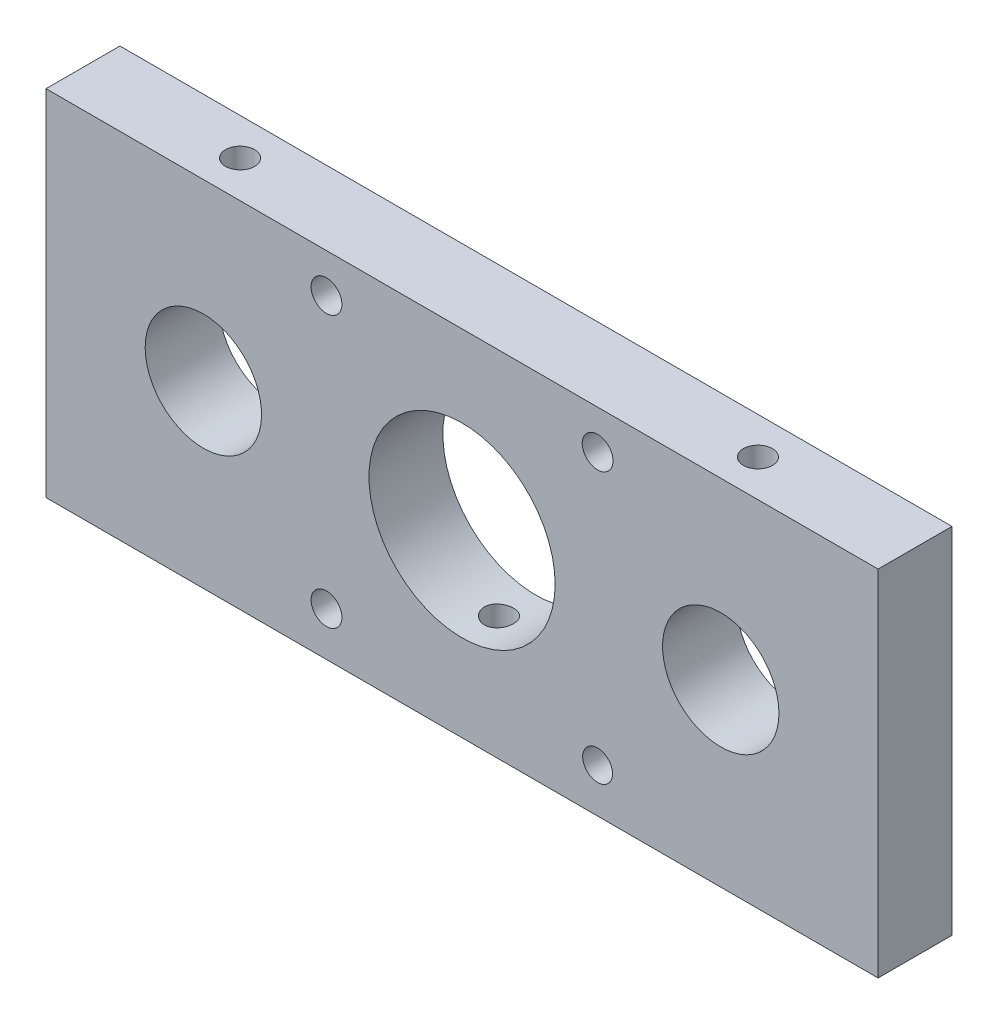
SolidWorks part; units mm, degrees
ref_plane "Plano frontal" through (0, 0, 0) normal (0, 0, 1) x (1, 0, 0)
ref_plane "Plano superior" through (0, 0, 0) normal (0, 1, 0) x (1, 0, 0)
ref_plane "Plano direito" through (0, 0, 0) normal (1, 0, 0) x (0, 0, -1)
sketch "Esboço1" plane through (0, 0, 0) normal (0, 0, 1) x (1, 0, 0)
  line L0 (71.505, 27) -> (-71.505, -27) construction
  line L1 (-71.505, 27) -> (71.505, 27)
  line L2 (-71.505, 27) -> (-71.505, -27)
  line L3 (-71.505, -27) -> (71.505, -27)
  line L4 (71.505, 27) -> (71.505, -27)
  dimension "D1" = 143.01
  dimension "D2" = 54
extrude "Ressalto-extrusão1" add sketch "Esboço1" along normal blind 10
sketch "Esboço14" plane through (-71.505, 0, 0) normal (-1, 0, 0) x (0, 0, 1)
  line L1 (0, 27) -> (-2.7, 27)
  line L2 (0, 27) -> (0, -30.87)
  line L3 (0, -30.87) -> (-2.7, -30.87)
  line L4 (-2.7, 27) -> (-2.7, -30.87)
  dimension "D1" = 2.7
extrude "Ressalto-extrusão3" add sketch "Esboço14" against normal up to surface (143.01 mm away) up to face at (71.505, 0, 5)
sketch "Esboço2" plane through (0, 0, 10) normal (0, 0, 1) x (1, 0, 0)
  circle A0 centre (0, 0) radius 16
  dimension "D1" = 32
extrude "Circulo rolamento" cut sketch "Esboço2" against normal blind 19
sketch "Esboço7" plane through (0, 0, 10) normal (0, 0, 1) x (1, 0, 0)
  line L0 (0, 0) -> (0, -27) construction
  line L1 (-71.505, -27) -> (71.505, -27) construction
  circle A0 centre (-44.465, 0) radius 10
  circle A1 centre (44.465, 0) radius 10
  dimension "D1" = 20
  dimension "D2" = 27.04
  dimension "D3" = 27
extrude "Corte-extrusão3" cut sketch "Esboço7" against normal blind 19
sketch "Esboço8" plane through (0, 0, 10) normal (0, 0, 1) x (1, 0, 0)
  line L1 (-71.505, -27) -> (71.505, -27)
  line L2 (-71.505, -27) -> (-71.505, -30.87)
  line L3 (-71.505, -30.87) -> (71.505, -30.87)
  line L4 (71.505, -27) -> (71.505, -30.87)
  dimension "D1" = 143.01
  dimension "D2" = 3.87
extrude "Ressalto-extrusão2" add sketch "Esboço8" against normal blind 10
sketch "Esboço22" plane through (0, 0, 10) normal (0, 0, 1) x (1, 0, 0)
  line L1 (-71.505, 27) -> (71.505, 27)
  line L2 (-71.505, 27) -> (-71.505, 30)
  line L3 (-71.505, 30) -> (71.505, 30)
  line L4 (71.505, 27) -> (71.505, 30)
  dimension "D1" = 3
extrude "Ressalto-extrusão4" add sketch "Esboço22" against normal up to surface (12.7 mm away) up to face at (-44.465, 10, -2.7)
sketch "Esboço9" plane through (0, 0, 10) normal (0, 0, 1) x (1, 0, 0)
  line L0 (23.3, -23.3) -> (23.3, 23.3) construction
  line L1 (23.3, 23.3) -> (-23.3, 23.3) construction
  line L2 (-23.3, 23.3) -> (-23.3, -23.3) construction
  line L3 (-23.3, -23.3) -> (23.3, -23.3) construction
  line L4 (23.3, 23.3) -> (-23.3, -23.3) construction
  line L5 (-71.505, -30.87) -> (71.505, -30.87) construction
  line L6 (0, 23.3) -> (0, 0) construction
  line L7 (71.505, -30.87) -> (71.505, 30) construction
  circle A3 centre (23.3, -23.3) radius 2.5685
  circle A4 centre (23.3, 23.3) radius 2.65
  circle A5 centre (-23.3, -23.3) radius 2.65
  circle A6 centre (-23.3, 23.3) radius 2.65
  dimension "D1" = 46.6
  dimension "D2" = 46.6
  dimension "D3" = 5.3
  dimension "D4" = 5.3
  dimension "D5" = 5.3
  dimension "D6" = 5.137
  dimension "D7" = 7.57
  dimension "D8" = 71.505
sketch "Esboço12" plane through (0, -30.87, 0) normal (0, -1, 0) x (1, 0, 0)
  line L0 (-71.505, 3.65) -> (71.505, 3.65) construction
  line L1 (-71.505, -2.7) -> (-71.505, 10) construction
  line L2 (71.505, -2.7) -> (71.505, 10) construction
  line L3 (0, 3.65) -> (0, -2.7) construction
  line L4 (71.505, -2.7) -> (-71.505, -2.7) construction
  circle A0 centre (-61.505, 3.65) radius 2.5
  circle A1 centre (33.505, 3.65) radius 2.5
  circle A2 centre (0, 3.65) radius 2.5
  circle A3 centre (-33.505, 3.65) radius 2.5
  circle A4 centre (61.505, 3.65) radius 2.5
  dimension "D1" = 5
  dimension "D2" = 5
  dimension "D3" = 5
  dimension "D4" = 10
  dimension "D5" = 38
extrude "Corte-extrusão6" cut sketch "Esboço12" against normal blind 17
extrude "Corte-extrusão15" cut sketch "Esboço9" against normal up to next
sketch "Esboço23" plane through (0, 30, 0) normal (0, 1, 0) x (1, 0, 0)
  line L0 (-71.505, -3.65) -> (71.505, -3.65) construction
  line L1 (-71.505, 2.7) -> (-71.505, -10) construction
  line L2 (71.505, 2.7) -> (71.505, -10) construction
  circle A0 centre (-44.505, -3.65) radius 2.5
  circle A1 centre (44.505, -3.65) radius 2.5
  dimension "D3" = 5
  dimension "D4" = 5
  dimension "D1" = 27
  dimension "D2" = 27
extrude "Corte-extrusão16" cut sketch "Esboço23" against normal up to next
